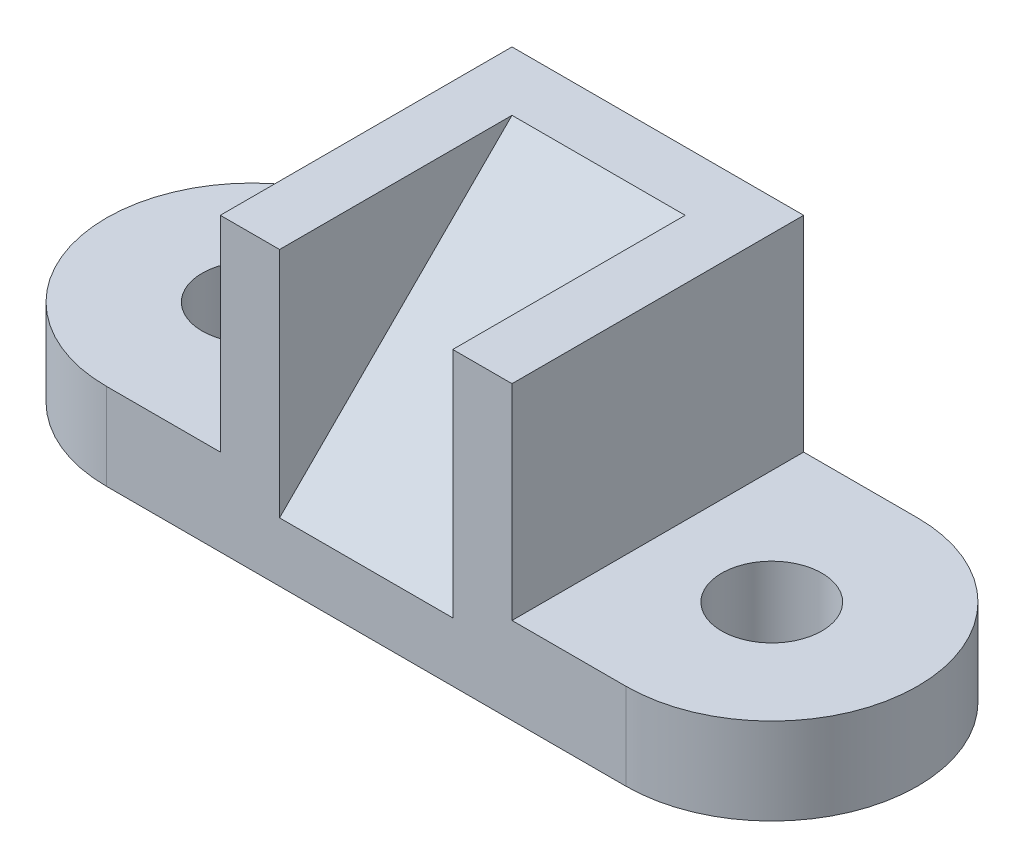
SolidWorks part; units mm, degrees
ref_plane "Front Plane" through (0, 0, 0) normal (0, 0, 1) x (1, 0, 0)
ref_plane "Top Plane" through (0, 0, 0) normal (0, 1, 0) x (1, 0, 0)
ref_plane "Right Plane" through (0, 0, 0) normal (1, 0, 0) x (0, 0, -1)
sketch "Sketch1" plane through (0, 0, 0) normal (0, 1, 0) x (1, 0, 0)
  line L0 (57, 77.8421) -> (57, -20.6842) construction
  line L1 (0, 0) -> (114, 0)
  line L2 (0, 0) -> (0, 64)
  line L3 (0, 64) -> (114, 64)
  line L4 (114, 0) -> (114, 64)
  line L5 (-68.5263, 32) -> (192.9474, 32) construction
  line L6 (0, -32.0825) -> (0, 96.0825) construction
  line L7 (114, -32.0825) -> (114, 96.0825) construction
  arc A0 (0, 64) -> (0, 0) centre (0, 32) ccw
  arc A1 (114, 64) -> (114, 0) centre (114, 32) cw
  circle A2 centre (0, 32) radius 11
  circle A3 centre (114, 32) radius 11
  point P16 (0, 32)
  dimension "D3" = 22
  dimension "D1" = 114
  dimension "D2" = 64
extrude "Boss-Extrude1" add sketch "Sketch1" along normal blind 19 contours A2 L2 A0 | L4 A3 L3 L2 A2 L1 | L4 A3 A1
sketch "Sketch2" plane through (0, 19, 0) normal (0, 1, 0) x (1, 0, 0)
  line L0 (0, 64) -> (114, 64) construction
  line L1 (25, 64) -> (89, 64)
  line L2 (25, 64) -> (25, 0)
  line L3 (25, 0) -> (89, 0)
  line L4 (89, 64) -> (89, 0)
  line L5 (0, 0) -> (114, 0) construction
  line L7 (38, 0) -> (76, 0)
  line L8 (38, 0) -> (38, 51)
  line L9 (38, 51) -> (76, 51)
  line L10 (76, 0) -> (76, 51)
  circle A0 centre (0, 32) radius 11 construction
  line M10 (114, 64) -> (0, 64)
  line M12 (0, 0) -> (114, 0)
  dimension "D1" = 64
  dimension "D2" = 25
  dimension "D3" = 13
  dimension "D4" = 13
  dimension "D5" = 13
extrude "Boss-Extrude2" add sketch "Sketch2" along normal blind 45 contours L10 L4 L2 L8 L9 M12 M10
sketch "Sketch3" plane through (0, 0, 0) normal (0, 0, 1) x (1, 0, 0)
  line L1 (38, 19) -> (76, 19)
  line L2 (38, 19) -> (38, 13)
  line L3 (38, 13) -> (76, 13)
  line L4 (76, 19) -> (76, 13)
  dimension "D1" = 38
  dimension "D2" = 6
extrude "Cut-Extrude1" cut sketch "Sketch3" against normal blind 51 contours L2 L1 L4 L3
sketch "Sketch4" plane through (76, 0, 0) normal (-1, 0, 0) x (0, 0, 1)
  line L0 (-51, 64) -> (0, 13)
sketch "Sketch5" plane through (76, 0, 0) normal (-1, 0, 0) x (0, 0, 1)
  line L0 (-51, 64) -> (-51, 13)
  line L1 (-51, 13) -> (0, 13)
  line L2 (0, 13) -> (-51, 64)
sketch "Sketch6" plane through (38, 0, 0) normal (1, 0, 0) x (0, 0, -1)
  line L0 (51, 64) -> (0, 13)
  line L1 (0, 13) -> (51, 13)
  line L2 (51, 13) -> (51, 64)
sketch "Sketch8" plane through (38, 0, 0) normal (1, 0, 0) x (0, 0, -1)
  line L0 (51, 64) -> (0, 13)
  line L1 (0, 13) -> (51, 13)
  line L2 (51, 13) -> (51, 64)
extrude "Boss-Extrude4" add sketch "Sketch8" along normal blind 38
